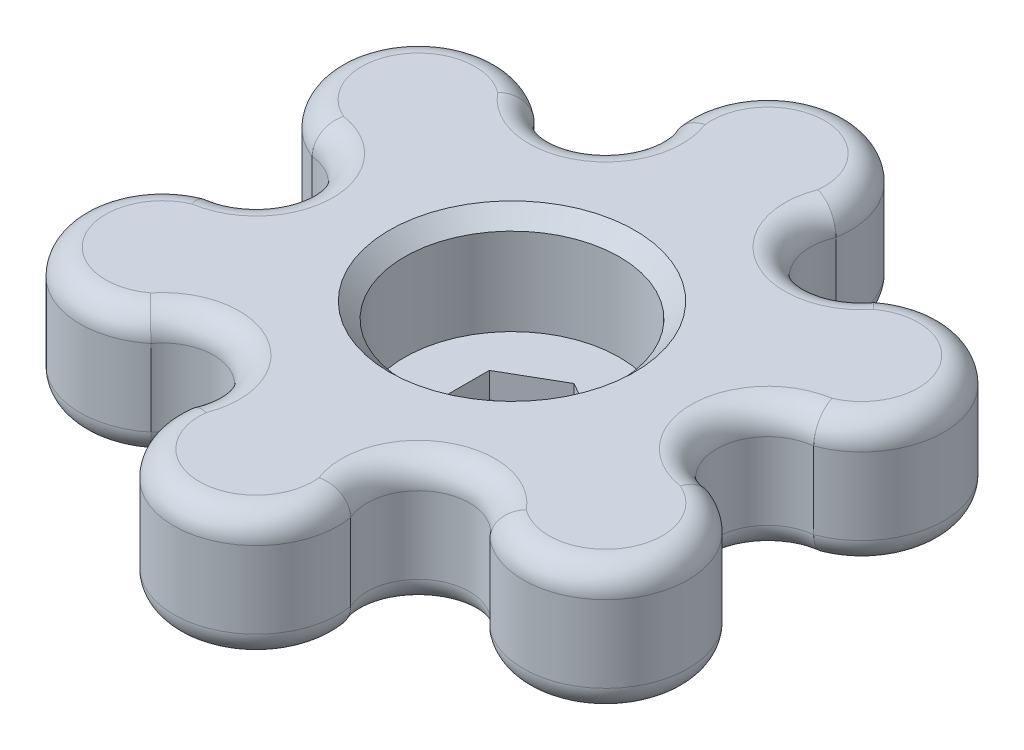
SolidWorks part; units mm, degrees
ref_plane "Front Plane" through (0, 0, 0) normal (0, 0, 1) x (1, 0, 0)
ref_plane "Top Plane" through (0, 0, 0) normal (0, 1, 0) x (1, 0, 0)
ref_plane "Right Plane" through (0, 0, 0) normal (1, 0, 0) x (0, 0, -1)
sketch "Sketch1" plane through (0, 0, 0) normal (0, 1, 0) x (1, 0, 0)
  line L0 (0, 8.5891) -> (0, 0) construction
  circle A0 centre (0, 0) radius 4.2
  arc A4 (3.1766, 9.482) -> (-3.1766, 9.482) centre (0, 10) ccw
  circle A5 centre (0, 0) radius 10 construction
  arc A6 (3.1766, 9.482) -> (6.6234, 7.4921) centre (5, 8.6603) ccw
  arc A7 (9.8, 1.99) -> (6.6234, 7.4921) centre (8.6603, 5) ccw
  arc A8 (9.8, 1.99) -> (9.8, -1.99) centre (10, 0) ccw
  arc A9 (6.6234, -7.4921) -> (9.8, -1.99) centre (8.6603, -5) ccw
  arc A10 (6.6234, -7.4921) -> (3.1766, -9.482) centre (5, -8.6603) ccw
  arc A11 (-3.1766, -9.482) -> (3.1766, -9.482) centre (0, -10) ccw
  arc A12 (-3.1766, -9.482) -> (-6.6234, -7.4921) centre (-5, -8.6603) ccw
  arc A13 (-9.8, -1.99) -> (-6.6234, -7.4921) centre (-8.6603, -5) ccw
  arc A14 (-9.8, -1.99) -> (-9.8, 1.99) centre (-10, 0) ccw
  arc A15 (-6.6234, 7.4921) -> (-9.8, 1.99) centre (-8.6603, 5) ccw
  arc A16 (-6.6234, 7.4921) -> (-3.1766, 9.482) centre (-5, 8.6603) ccw
  dimension "D1" = 8.4
  dimension "D2" = 20
  dimension "D3" = 6
  dimension "D4" = 2
extrude "Boss-Extrude1" add sketch "Sketch1" along normal blind 5
sketch "Sketch2" plane through (0, 0, 0) normal (0, -1, 0) x (1, 0, 0)
  line L1 (0, 2.4249) -> (-2.1, 1.2124)
  line L2 (-2.1, 1.2124) -> (-2.1, -1.2124)
  line L3 (-2.1, -1.2124) -> (0, -2.4249)
  line L4 (0, -2.4249) -> (2.1, -1.2124)
  line L5 (2.1, -1.2124) -> (2.1, 1.2124)
  line L6 (2.1, 1.2124) -> (0, 2.4249)
  circle A0 centre (0, 0) radius 4.2 construction
  circle A1 centre (0, 0) radius 4.2
  circle A2 centre (0, 0) radius 2.1 construction
  dimension "D1" = 4.2
extrude "Boss-Extrude2" add sketch "Sketch2" against normal blind 1
fillet "Fillet1" radius 1 12 edges at (-11.4476, 0, -6.6093) (-8, 0, 0) (-11.4476, 0, 6.6093) (-4, 0, 6.9282) (0, 0, 13.2186) (4, 0, 6.9282) (11.4476, 0, 6.6093) (8, 0, 0) (11.4476, 0, -6.6093) (4, 0, -6.9282) (-4, 0, -6.9282) (0, 0, -13.2186)
chamfer "Chamfer1" distance 0.6 angle 45 1 edges at (0, 5, 4.2)
fillet "Fillet2" radius 1 12 edges at (0, 5, -13.2186) (4, 5, -6.9282) (11.4476, 5, -6.6093) (8, 5, 0) (11.4476, 5, 6.6093) (4, 5, 6.9282) (0, 5, 13.2186) (-4, 5, 6.9282) (-11.4476, 5, 6.6093) (-8, 5, 0) (-4, 5, -6.9282) (-11.4476, 5, -6.6093)
